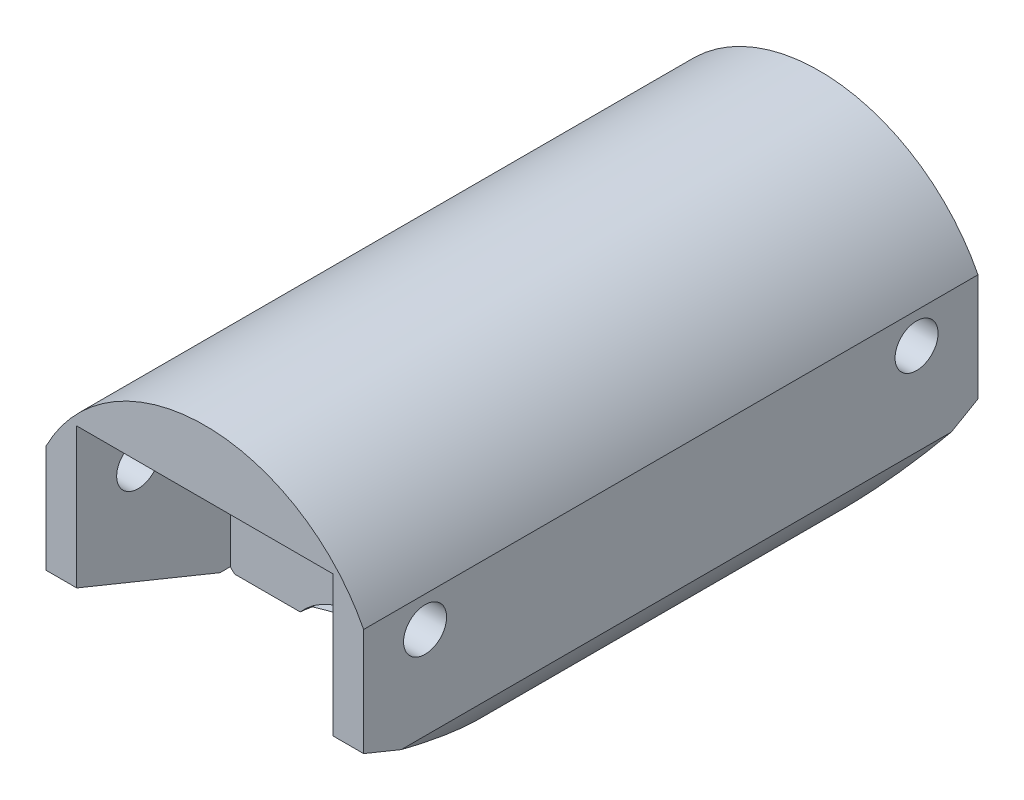
SolidWorks part; units mm, degrees
material "PET"
ref_plane "Front Plane" through (0, 0, 0) normal (0, 0, 1) x (1, 0, 0)
ref_plane "Top Plane" through (0, 0, 0) normal (0, 1, 0) x (1, 0, 0)
ref_plane "Right Plane" through (0, 0, 0) normal (1, 0, 0) x (0, 0, -1)
sketch "Sketch1" plane through (0, 0, 0) normal (0, 0, 1) x (1, 0, 0)
  line L0 (0, 0) -> (0, 5.08)
  line L3 (13.1318, 5.08) -> (13.1318, 0)
  arc A2 (0, 5.08) -> (13.1318, 5.08) centre (6.5659, 1.7387) cw
  arc A3 (0, 0) -> (13.1318, 0) centre (6.5659, 3.3413) ccw
  point P7 (6.5659, -4.0259)
  point P8 (6.5659, 9.1059)
extrude "Boss-Extrude1" add sketch "Sketch1" along normal mid plane 25.4 contours A2 L3 A3 L0
sketch "Sketch2" plane through (0, 0, 0) normal (1, 0, 0) x (0, 0, -1)
  line L4 (15.875, 2.54) -> (-49984.125, 2.54) construction
  line L5 (12.7, 5.08) -> (12.7, 0) construction
  line L6 (-12.7, 5.08) -> (-12.7, 0) construction
  line L7 (-12.7, -4.0259) -> (-12.7, 0.635)
  line L8 (-1.27, -4.0259) -> (-12.7, -4.0259)
  line L9 (-12.7, 0.635) -> (-1.27, -4.0259)
  line L10 (0, -1000) -> (0, 49000) construction
  line L18 (12.7, 0.635) -> (12.7, -4.0259)
  line L19 (-10.16, 1.27) -> (-12.7, 1.27)
  line L21 (-10.16, 3.81) -> (-12.7, 3.81)
  line L22 (-12.7, 1.27) -> (-12.7, 3.81)
  line L23 (-15.0884, 2.54) -> (-12.7, 3.81) construction
  line L24 (-15.0884, 2.54) -> (-12.7, 1.27) construction
  line L27 (10.16, 1.27) -> (12.7, 1.27)
  line L28 (12.7, 1.27) -> (12.7, 3.81)
  line L29 (10.16, 3.81) -> (12.7, 3.81)
  line L30 (12.7, -4.0259) -> (4.6271, -4.0259)
  line L31 (-12.7, -4.0259) -> (12.7, -4.0259) construction
  line L32 (4.6271, -4.0259) -> (12.7, 0.635)
  line L33 (-12.7, 9.1059) -> (-12.7, 5.08) construction
  arc A3 (-10.16, 3.81) -> (-10.16, 1.27) centre (-7.9603, 2.54) cw
  arc A4 (10.16, 3.81) -> (10.16, 1.27) centre (7.9603, 2.54) ccw
  point P0 (-15.0884, 2.54)
  point P11 (12.7, 2.54)
  point P14 (-12.7, 2.54)
  point P26 (-12.7, 2.54)
extrude "Cut-Extrude1" cut sketch "Sketch2" along normal through all
sketch "Sketch3" plane through (0, 0, 12.7) normal (0, 0, 1) x (1, 0, 0)
  line L3 (-14.803, 2.54) -> (33.5586, 2.54) construction
  line L4 (6.5659, 9.0576) -> (6.5659, -4.0259) construction
  line L5 (16.1544, 2.54) -> (0, 2.54) construction
  line L6 (13.1318, 2.54) -> (0, 2.54) construction
  line L7 (0, 5.08) -> (0, 0) construction
  arc A7 (0, 0) -> (13.1318, 0) centre (6.5659, 3.3413) ccw construction
  arc A9 (12.9061, 1.0311) -> (0.7401, 0.2126) centre (6.5659, 4.445) cw
  arc A13 (3.9299, -2.2561) -> (9.2019, -2.2561) centre (6.5659, -4.0259) cw
  dimension "D1" = 1.27
  dimension "D2" = 3.175
  dimension "D3" = 1.5089
  dimension "D4" = 12.166
  dimension "D5" = 1.905
extrude "Cut-Extrude2" cut sketch "Sketch3" against normal through all contours A13 A9
sketch "Sketch4" plane through (0, 0, 0) normal (-1, 0, 0) x (0, 0, 1)
  line L0 (12.7, 1.27) -> (10.16, 1.27) construction
  line L1 (10.16, 3.81) -> (12.7, 3.81) construction
  line L2 (-10.16, 1.27) -> (-12.7, 1.27) construction
  line L3 (-12.7, 3.81) -> (-10.16, 3.81) construction
  line L4 (12.7, 1.27) -> (10.16, 1.27)
  line L5 (10.16, 3.81) -> (12.7, 3.81)
  line L6 (-10.16, 1.27) -> (-12.7, 1.27)
  line L7 (-12.7, 3.81) -> (-10.16, 3.81)
  line L8 (-12.7, 3.81) -> (-12.7, 1.27)
  line L9 (12.7, 3.81) -> (12.7, 1.27)
  arc A0 (7.9603, 0) -> (10.16, 1.27) centre (7.9603, 2.54) ccw construction
  arc A1 (10.16, 3.81) -> (7.9603, 5.08) centre (7.9603, 2.54) ccw construction
  arc A2 (7.9603, 5.08) -> (7.9603, 0) centre (7.9603, 2.54) ccw construction
  arc A3 (-10.16, 1.27) -> (-7.9603, 0) centre (-7.9603, 2.54) ccw construction
  arc A4 (-7.9603, 5.08) -> (-10.16, 3.81) centre (-7.9603, 2.54) ccw construction
  arc A5 (-7.9603, 0) -> (-7.9603, 5.08) centre (-7.9603, 2.54) ccw construction
  arc A6 (7.9603, 0) -> (10.16, 1.27) centre (7.9603, 2.54) ccw
  arc A7 (10.16, 3.81) -> (7.9603, 5.08) centre (7.9603, 2.54) ccw
  arc A8 (7.9603, 5.08) -> (7.9603, 0) centre (7.9603, 2.54) ccw
  arc A9 (-10.16, 1.27) -> (-7.9603, 0) centre (-7.9603, 2.54) ccw
  arc A10 (-7.9603, 5.08) -> (-10.16, 3.81) centre (-7.9603, 2.54) ccw
  arc A11 (-7.9603, 0) -> (-7.9603, 5.08) centre (-7.9603, 2.54) ccw
extrude "Boss-Extrude2" add sketch "Sketch4" against normal up to surface (13.1318 mm away) up to face at (13.1318, 2.54, 0)
ref_plane "Plane1" through (5.08, 0, 0) normal (-1, 0, 0) x (0, 0, 1)
ref_plane "Plane2" through (6.5659, 0, 0) normal (1, 0, 0) x (0, 0, -1)
sketch "Sketch7" plane through (5.08, 0, 0) normal (-1, 0, 0) x (0, 0, 1)
  line L0 (-12.7, 0) -> (-12.7, 2.8575)
  line L1 (-12.7, 0.635) -> (-12.7, 5.08) construction
  line L2 (-12.7, 2.8575) -> (-10.16, 2.8575)
  line L4 (11.1428, 0) -> (-11.6001, 0) construction
  line L5 (-10.16, 0) -> (-12.7, 0)
  line L6 (-12.7, 2.8575) -> (-12.7, 0) construction
  line L7 (-10.16, 0) -> (-12.7, 0) construction
  line L8 (-10.16, 2.8575) -> (-10.16, 0)
  dimension "D1" = 2.54
extrude "Cut-Extrude3" cut sketch "Sketch7" along normal blind 2.54
sketch "Sketch9" plane through (0, 2.8575, 0) normal (0, -1, 0) x (1, 0, 0)
  line L0 (2.54, -10.16) -> (2.54, -12.7) construction
  line L1 (5.08, -12.7) -> (2.54, -12.7)
  line L2 (5.08, -12.7) -> (5.08, -8.89)
  line L3 (5.08, -8.89) -> (2.54, -8.89)
  line L4 (2.54, -12.7) -> (2.54, -8.89)
  line L5 (5.08, -10.16) -> (5.08, -12.7) construction
  line L6 (2.54, -12.7) -> (5.08, -12.7) construction
  dimension "D1" = 3.81
extrude "Cut-Extrude5" cut sketch "Sketch9" along normal through all
sketch "Sketch11" plane through (0, 2.8575, 0) normal (0, -1, 0) x (1, 0, 0)
  line L4 (5.08, -12.7) -> (5.08, -8.89)
  line L5 (5.08, -8.89) -> (2.54, -8.89)
  line L6 (2.54, -8.89) -> (2.54, -12.7)
  line L7 (2.54, -12.7) -> (5.08, -12.7)
  line L8 (5.08, -12.7) -> (5.08, -8.89)
  line L9 (5.08, -8.89) -> (2.54, -8.89)
  line L10 (2.54, -8.89) -> (2.54, -12.7)
  line L11 (2.54, -12.7) -> (5.08, -12.7)
  dimension "D1" = 0
extrude "Cut-Extrude8" cut sketch "Sketch11" against normal blind 2.54
sketch "Sketch12" plane through (2.54, 0, 0) normal (1, 0, 0) x (0, 0, -1)
  line L4 (8.89, -1.5647) -> (12.7, 0.635)
  line L5 (12.7, 0.635) -> (12.7, 5.3975)
  line L6 (12.7, 5.3975) -> (8.89, 5.3975)
  line L7 (8.89, 5.3975) -> (8.89, -1.5647)
  line L8 (8.89, -1.5647) -> (12.7, 0.635)
  line L10 (12.7, 0.635) -> (12.7, 5.3975)
  line L11 (12.7, 5.3975) -> (8.89, 5.3975)
  line L12 (8.89, 5.3975) -> (8.89, -1.5647)
  dimension "D1" = 0
extrude "Cut-Extrude9" cut sketch "Sketch12" against normal blind 1.27
sketch "Sketch13" plane through (0, 0, -8.89) normal (0, 0, -1) x (-1, 0, 0)
  line L10 (-1.27, 6.4377) -> (-11.8618, 6.4377)
  line L13 (-11.8618, -4.0259) -> (-1.27, -4.0259)
  line L14 (-1.27, -1.5647) -> (-1.27, 0.635) construction
  line L15 (-1.27, -4.0259) -> (-1.27, 6.4377)
  line L17 (-11.8618, 6.4377) -> (-11.8618, -4.0259)
  line L20 (-13.1318, 5.08) -> (-13.1318, 0.635) construction
  arc A0 (0, 5.08) -> (-13.1318, 5.08) centre (-6.5659, 1.7387) ccw construction
  arc A2 (-13.1318, 0) -> (0, 0) centre (-6.5659, 3.3413) ccw construction
  line M6 (-1.27, -1.5647) -> (-1.27, 5.3975)
  line M7 (-1.27, 5.3975) -> (-5.08, 5.3975)
  line M12 (-5.08, 5.3975) -> (-5.08, -1.2201)
  dimension "D3" = 1.27
  dimension "D1" = 4.699
extrude "Cut-Extrude10" cut sketch "Sketch13" against normal blind 2.54 and the other way blind 10 contours L13 M12 M6 M7
sketch "Sketch10" plane through (0, 0, 0) normal (-1, 0, 0) x (0, 0, 1)
  line L0 (-12.7, 3.81) -> (-12.7, 0) construction
  line L1 (-12.7, 0.635) -> (-12.7, 5.08) construction
  line L2 (-12.7, 0) -> (-16.3757, 0) construction
  line L4 (11.1428, 0) -> (-11.6001, 0) construction
  circle A1 centre (-10.16, 3.81) radius 0.889
  dimension "D1" = 2.54
  dimension "D2" = 1.778
  dimension "D4" = 3.81
extrude "Cut-Extrude7" cut sketch "Sketch10" against normal through all
ref_plane "Plane3" through (0, 0, 0) normal (0, 0, -1) x (-1, 0, 0)
mirror "Mirror1" about plane through (0, 0, 0) normal (0, 0, -1) of "Cut-Extrude7", "Cut-Extrude10"
sketch "Sketch14" plane through (0, 0, 6.35) normal (0, 0, 1) x (1, 0, 0)
  line L0 (1.27, -0.8509) -> (11.8618, -0.8509) construction
  line L1 (3.8989, 5.3385) -> (9.2329, 5.3385) construction
  line L2 (3.8989, 5.3385) -> (3.8989, -0.3511) construction
  line L3 (3.8989, -0.3511) -> (9.2329, -0.3511) construction
  line L4 (9.2329, 5.3385) -> (9.2329, -0.3511) construction
  line L5 (3.8989, 5.3385) -> (9.2329, -0.3511) construction
  line L6 (3.8989, -0.3511) -> (9.2329, 5.3385) construction
  line L7 (1.27, 0.635) -> (1.27, -1.7801) construction
  line L8 (11.8618, 6.4377) -> (11.8618, -1.7801) construction
  line L9 (8.5979, 4.9575) -> (9.2329, 4.9575) construction
  line L10 (8.5979, 5.3385) -> (9.2329, 5.3385)
  line L11 (8.5979, 4.5765) -> (9.2329, 4.5765)
  arc A0 (8.972, -1.9544) -> (4.1598, -1.9544) centre (6.5659, -4.0259) ccw construction
  arc A2 (8.5979, 5.3385) -> (8.5979, 4.5765) centre (8.5979, 4.9575) ccw
  arc A3 (9.2329, 4.5765) -> (9.2329, 5.3385) centre (9.2329, 4.9575) ccw
  point P0 (6.5659, 2.4937)
  point P8 (6.5659, -0.8509)
  point P15 (8.9154, 4.9575)
  dimension "D5" = 0.3511
  dimension "D1" = 5.334
  dimension "D2" = 5.6896
  dimension "D3" = 0.762
  dimension "D4" = 0.635
extrude "Cut-Extrude11" cut sketch "Sketch14" against normal blind 17.78
sketch "Sketch15" plane through (0, 0, -6.35) normal (0, 0, -1) x (-1, 0, 0)
  line L1 (-9.2329, -0.2118) -> (-3.8989, -0.2118) construction
  line L2 (-9.2329, -0.2118) -> (-9.2329, 5.4778) construction
  line L3 (-9.2329, 5.4778) -> (-3.8989, 5.4778) construction
  line L4 (-3.8989, -0.2118) -> (-3.8989, 5.4778) construction
  line L5 (-9.2329, -0.2118) -> (-3.8989, 5.4778) construction
  line L6 (-9.2329, 5.4778) -> (-3.8989, -0.2118) construction
  line L7 (-4.9149, 5.0968) -> (-4.2799, 5.0968) construction
  line L8 (-4.9149, 5.4778) -> (-4.2799, 5.4778)
  line L9 (-4.9149, 4.7158) -> (-4.2799, 4.7158)
  line L10 (-2.869, -3.0312) -> (-10.2628, -3.0312) construction
  arc A0 (-3.9299, -2.2561) -> (-9.2019, -2.2561) centre (-6.5659, -4.0259) ccw construction
  arc A1 (-4.9149, 5.4778) -> (-4.9149, 4.7158) centre (-4.9149, 5.0968) ccw
  arc A2 (-4.2799, 4.7158) -> (-4.2799, 5.4778) centre (-4.2799, 5.0968) ccw
  point P0 (-6.5659, 2.633)
  point P8 (-6.5659, -0.8509)
  point P13 (-4.5974, 5.0968)
  dimension "D1" = 5.6896
  dimension "D2" = 5.334
  dimension "D3" = 0.762
  dimension "D4" = 0.635
  dimension "D5" = 8.509
extrude "Cut-Extrude12" cut sketch "Sketch15" against normal blind 15.875
sketch "Sketch16" plane through (0, 0, 0) normal (-1, 0, 0) x (0, 0, 1)
  text T0 "Pinky 2\r\n"
extrude "Cut-Extrude13" cut sketch "Sketch16" against normal blind 1
equation "\"D1@Sketch1\"=0.517"
equation "\"D2@Sketch1\"=0.517"
equation "\"D1@Boss-Extrude1\"=1"
equation "\"D2@Sketch2\"=0.1"
equation "\"D3@Sketch2\"=0.1"
